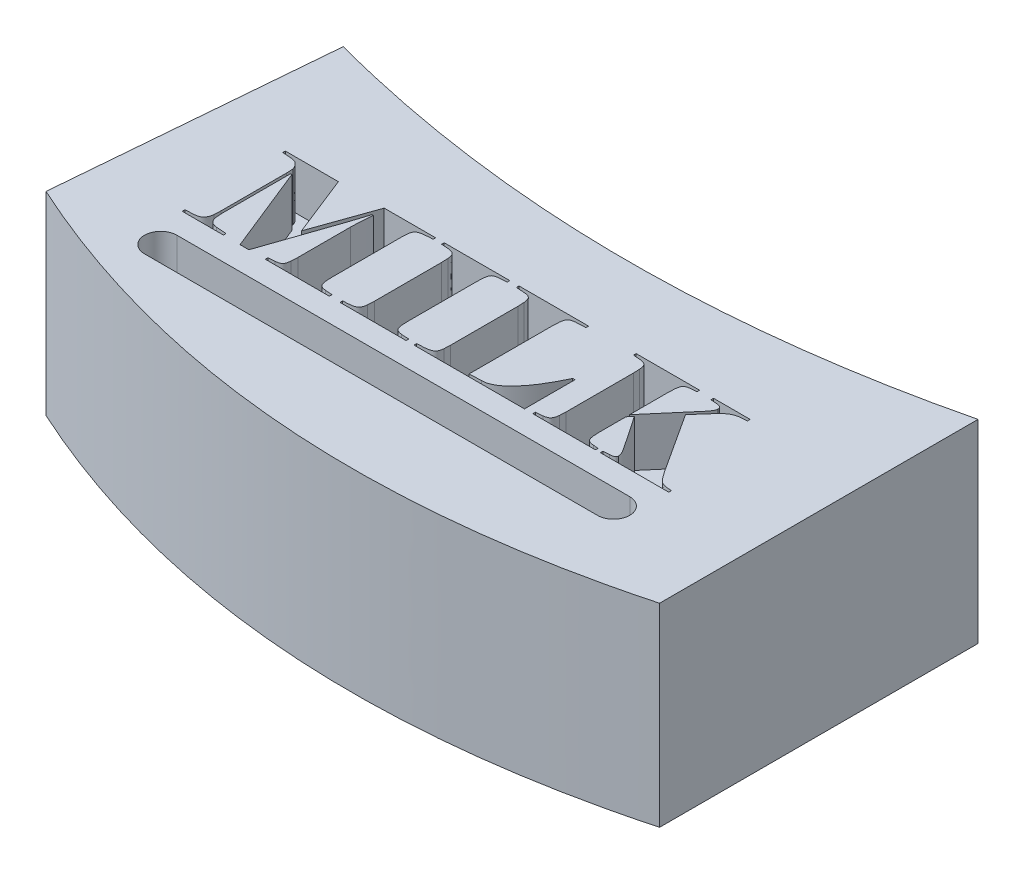
SolidWorks part; units mm, degrees
ref_plane "Front Plane" through (0, 0, 0) normal (0, 0, 1) x (1, 0, 0)
ref_plane "Top Plane" through (0, 0, 0) normal (0, 1, 0) x (1, 0, 0)
ref_plane "Right Plane" through (0, 0, 0) normal (1, 0, 0) x (0, 0, -1)
sketch "Sketch1" plane through (0, 0, 0) normal (0, 1, 0) x (1, 0, 0)
  line L0 (104.175, 42.1741) -> (104.175, -7.8279)
  spline S0 degree 2 poles (0, 0) (49.4176, -22.5538) (104.175, -7.8279) knots 0 0 0 1 1 1
  spline S1 degree 1 poles (0, 0) (3.6505, 43.0254) knots 0 0 1 1
  spline S2 degree 2 poles (3.6505, 43.0254) (53.0879, 29.8327) (104.175, 42.1741) knots 0 0 0 1 1 1
  dimension "D1" = 106.68
  dimension "D2" = 43.18
  dimension "D3" = 101.6
  dimension "D4" = 50.002
extrude "Boss-Extrude1" add sketch "Sketch1" along normal blind 30.48
sketch "Sketch2" plane through (0, 30.48, 0) normal (0, 1, 0) x (1, 0, 0)
  line L0 (-0.3817, 5.4394) -> (0.4646, 5.4763) construction
  line L1 (3.6505, 43.0254) -> (0, 0) construction
  line L2 (0.4646, 5.4763) -> (104.175, 5.4763) construction
  line L3 (104.175, -7.8279) -> (104.175, 42.1741) construction
  line L4 (31.4306, 5.4763) -> (31.4306, 37.6435) construction
  line L5 (75.3726, 37.2319) -> (75.3726, 5.4763) construction
  line L6 (31.4306, 56.2763) -> (75.3726, 56.2763) construction
  parabola Q0 (104.175, 42.1741) -> (3.6505, 43.0254) focus (48.8039, 134.8436) apex (42.4578, 36.6191) construction
  parabola Q1 (104.175, 42.1741) -> (3.6505, 43.0254) focus (48.8039, 134.8436) apex (42.4578, 36.6191) construction
  text T0 "MILK" font "Elephant" height in points 48
  dimension "D1" = 43.942
  dimension "D2" = 50.8
extrude "Cut-Extrude1" cut sketch "Sketch2" against normal blind 7.62
sketch "Sketch5" plane through (0, 0, 0) normal (0, -1, 0) x (1, 0, 0)
  text T0 "Will Buziak, Group M"
extrude "Cut-Extrude2" cut sketch "Sketch5" against normal blind 7.62
sketch "Sketch6" plane through (0, 30.48, 0) normal (0, 1, 0) x (1, 0, 0)
  line L0 (16.2264, 1.7829) -> (87.3464, 1.7829) construction
  line L1 (16.2264, 4.3229) -> (87.3464, 4.3229)
  line L2 (16.2264, -0.7571) -> (87.3464, -0.7571)
  arc A0 (16.2264, 4.3229) -> (16.2264, -0.7571) centre (16.2264, 1.7829) ccw
  arc A1 (87.3464, -0.7571) -> (87.3464, 4.3229) centre (87.3464, 1.7829) ccw
  point P2 (51.7864, 1.7829)
  dimension "D2" = 2.54
  dimension "D1" = 71.12
extrude "Cut-Extrude3" cut sketch "Sketch6" against normal blind 15.24
